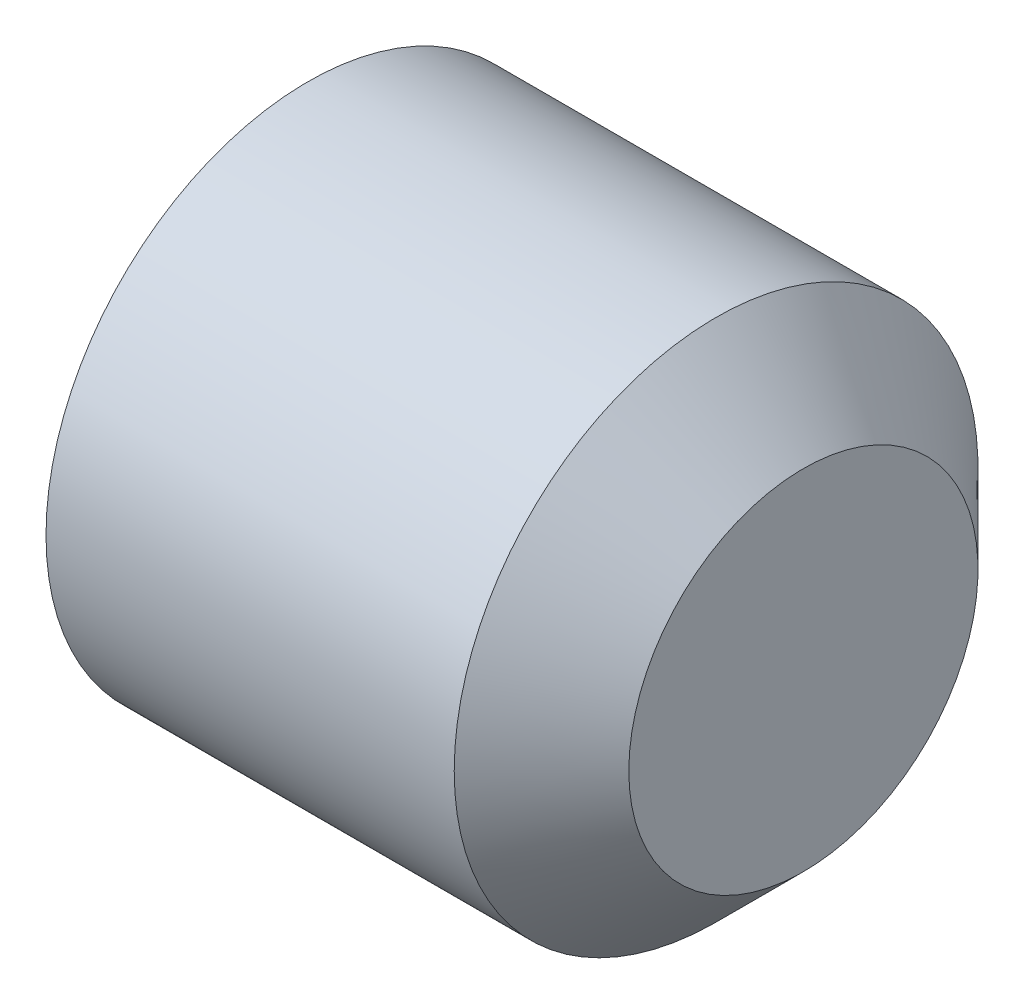
SolidWorks part; units mm, degrees
ref_plane "Plane1" through (0, 0, 0) normal (0, 0, 1) x (1, 0, 0)
ref_plane "Plane2" through (0, 0, 0) normal (0, 1, 0) x (1, 0, 0)
ref_plane "Plane3" through (0, 0, 0) normal (1, 0, 0) x (0, 0, -1)
sketch "BodySke" plane through (0, 0, 0) normal (0, 0, 1) x (1, 0, 0)
  line L0 (0, 0) -> (0, 1.2195)
  line L1 (0, 1.2195) -> (0.1619, 1.5)
  line L2 (0.1619, 1.5) -> (2.5, 1.5)
  line L3 (2.5, 1.5) -> (3, 1)
  line L4 (3, 0) -> (0, 0)
  line L5 (-12.7, 0) -> (88.9, 0) construction
  line L6 (3, 1) -> (3, 0)
  line L7 (3, 1) -> (3, 10.525) construction
  line L8 (0, -1.2195) -> (0.1619, -1.5) construction
  line L9 (0.5, 15.875) -> (0.5, -3.175) construction
  line L10 (2.5, -1.5) -> (3, -1) construction
  dimension "Length" = 3
  dimension "Diameter" = 3
  dimension "Drive_ch_ang" = 60
  dimension "Minor_dia" = 2.439
  dimension "Cup_nose_ang" = 45
  dimension "Cup_dia" = 2
  dimension "Advance" = 0.5
revolve "BaseBody" add sketch "BodySke" angle 360 about L5
cosmetic thread "ThreadCosmetic" parameters "Thread_minor"=2.439
sketch "Sketch2" plane through (0, 0, 0) normal (-1, 0, 0) x (0, 0, 1)
  line L0 (0.433, 0.75) -> (-0.433, 0.75)
  line L1 (-0.433, 0.75) -> (-0.866, 0)
  line L2 (0.433, 0.75) -> (0.866, 0)
  line L3 (0.433, -0.75) -> (0.866, 0)
  line L4 (0.433, -0.75) -> (-0.433, -0.75)
  line L5 (-0.433, -0.75) -> (-0.866, 0)
  dimension "Hex_size" = 1.5
  dimension "D2" = 0.75
  dimension "D3" = 0.75
extrude "Hex" cut sketch "Sketch2" against normal blind 1.5
sketch "Sketch4" plane through (0, 4.7709, -0.5249) normal (-1, 0, 0) x (0, 0, 1)
  line L0 (0.5249, -4.7709) -> (1.3124, -4.7709)
  line L1 (0.5249, -4.7709) -> (6.6732, -1.2211) construction
  line L2 (0.5249, -4.7709) -> (0.9186, -4.0889)
  line L3 (1.153, -4.6137) -> (1.2782, -4.5415)
  line L4 (0.975, -4.3054) -> (1.1002, -4.2332)
  arc A0 (1.153, -4.6137) -> (0.975, -4.3054) centre (0.5249, -4.7709) ccw
  arc A1 (1.3124, -4.7709) -> (1.2782, -4.5415) centre (0.5249, -4.7709) ccw
  arc A2 (0.9186, -4.0889) -> (1.1002, -4.2332) centre (0.5249, -4.7709) cw
  circle A3 centre (0.5249, -4.7709) radius 0.6475 construction
  circle A4 centre (0.5249, -4.7709) radius 0.7875 construction
  dimension "D1" = 30
  dimension "Spline_n_dim" = 1.295
  dimension "Spline_m_dim" = 1.575
  dimension "Spline_a_dim" = 60
  dimension "D3" = 0.178
  dimension "Spline_p_dim" = 0.356
extrude "Spline6" [suppressed] cut sketch "Sketch4" against normal blind 1.2
pattern_circular "CirPattern1" [suppressed] count 6 every 60 about axis through (-12.7, 0, 0) along (1, 0, 0)
sketch "Sketch5" plane through (0, 0.6556, 6.6316) normal (-1, 0, 0) x (0, 0, 1)
  line L0 (-6.6316, -0.6556) -> (-5.8441, -0.6556)
  line L1 (-6.6316, -0.6556) -> (-1.6115, 4.3645) construction
  line L2 (-6.6316, -0.6556) -> (-6.6316, 0.1319)
  line L3 (-6.0479, -0.3236) -> (-5.9633, -0.239)
  line L4 (-6.2996, -0.0719) -> (-6.215, 0.0127)
  line L5 (-6.2996, -0.0719) -> (-6.0479, -0.3236)
  arc A1 (-5.8441, -0.6556) -> (-5.9633, -0.239) centre (-6.6316, -0.6556) ccw
  arc A2 (-6.6316, 0.1319) -> (-6.215, 0.0127) centre (-6.6316, -0.6556) cw
  circle A3 centre (-6.6316, -0.6556) radius 0.6475 construction
  circle A4 centre (-6.6316, -0.6556) radius 0.7875 construction
  dimension "D1" = 45
  dimension "Spline_n_dim" = 1.295
  dimension "Spline_m_dim" = 1.575
  dimension "Spline_a_dim" = 90
  dimension "D3" = 0.178
  dimension "Spline_p_dim" = 0.356
extrude "Spline4" [suppressed] cut sketch "Sketch5" against normal blind 1.2
pattern_circular "CirPattern2" [suppressed] count 4 every 90 about axis through (-12.7, 0, 0) along (1, 0, 0)
sketch "ThdSchSke" plane through (0, 0, 0) normal (0, 0, 1) x (1, 0, 0)
  line L0 (0.1619, -1.2195) -> (-0.0345, -1.5)
  line L1 (0.1619, -1.2195) -> (0.3584, -1.5)
  line L2 (0.3584, -1.5) -> (0.3584, -1.875)
  line L3 (-3.175, 0) -> (5.1513, 0) construction
  line L4 (0.1619, 1.5) -> (0.1619, -1.5) construction
  line L5 (0.3584, -1.875) -> (-0.0345, -1.875)
  line L6 (-0.0345, -1.875) -> (-0.0345, -1.5)
  dimension "Thread_minor" = 2.439
  dimension "Diameter" = 3
  dimension "SideAngle" = 55
  dimension "VeeAngle" = 70
  dimension "Overcut" = 3.75
revolve "ThreadSchematic" [suppressed] cut sketch "ThdSchSke" angle 360 about L3
pattern_linear "ThdSchPat" [suppressed]
equation "\"D2@Sketch2\" = \"Hex_size@Sketch2\" / 2"
equation "\"D3@Sketch2\" = \"Hex_size@Sketch2\" / 2"
equation "\"Thread_minor@ThreadCosmetic\" = \"Minor_dia@BodySke\""
equation "\"D1@Sketch4\" = \"Spline_a_dim@Sketch4\" / 2"
equation "\"D3@Sketch4\" = \"Spline_p_dim@Sketch4\" / 2"
equation "\"D2@CirPattern1\" = \"Spline_a_dim@Sketch4\""
equation "\"Num_teeth@CirPattern1\" = 360 / \"D2@CirPattern1\""
equation "\"Spline_a_dim@Sketch5\" = 90"
equation "\"Spline_p_dim@Sketch5\" = \"Spline_p_dim@Sketch4\""
equation "\"Spline_m_dim@Sketch5\" = \"Spline_m_dim@Sketch4\""
equation "\"Spline_n_dim@Sketch5\" = \"Spline_n_dim@Sketch4\""
equation "\"D1@Sketch5\" = \"Spline_a_dim@Sketch5\" / 2"
equation "\"D3@Sketch5\" = \"Spline_p_dim@Sketch5\" / 2"
equation "\"Key_eng@Spline4\" = \"Key_eng@Spline6\""
equation "\"Thread_minor@ThdSchSke\" = \"Thread_minor@ThreadCosmetic\""
equation "\"Diameter@ThdSchSke\" = \"Diameter@BodySke\""
equation "\"Overcut@ThdSchSke\" = \"Diameter@BodySke\" * 1.25"
equation "\"Num_threads@ThdSchPat\" = int( (\"Length@BodySke\" - ( ( ( \"Diameter@BodySke\" - \"Minor_dia@BodySke\" ) * 0.5 ) / tan( \"Drive_ch_ang@BodySke\" * 0.017453292 ) ) - ( ( ( \"Diameter@BodySke\" - \"Cup_dia@BodySke\" ) * 0.5 ) * tan( \"Cup_nose_ang@BodySke\" * 0.017453292 ) ) ) / \"Advance@BodySke\" + 0.999 )  + 1"
equation "\"Advance@ThdSchPat\" = (\"Length@BodySke\" - ( ( ( \"Diameter@BodySke\" - \"Minor_dia@BodySke\" ) * 0.5 ) / tan( \"Drive_ch_ang@BodySke\" * 0.017453292 ) ) - ( ( ( \"Diameter@BodySke\" - \"Cup_dia@BodySke\" ) * 0.5 ) * tan( \"Cup_nose_ang@BodySke\" * 0.017453292 ) ) ) /  (\"Num_threads@ThdSchPat\" - 1) 'relax it"
equation "' \"Num_threads@ThdSchPat\" = \"Num_threads@ThdSchPat\" - sgn( \"Num_threads@ThdSchPat\" - 1) '---chamfered tips only---"
